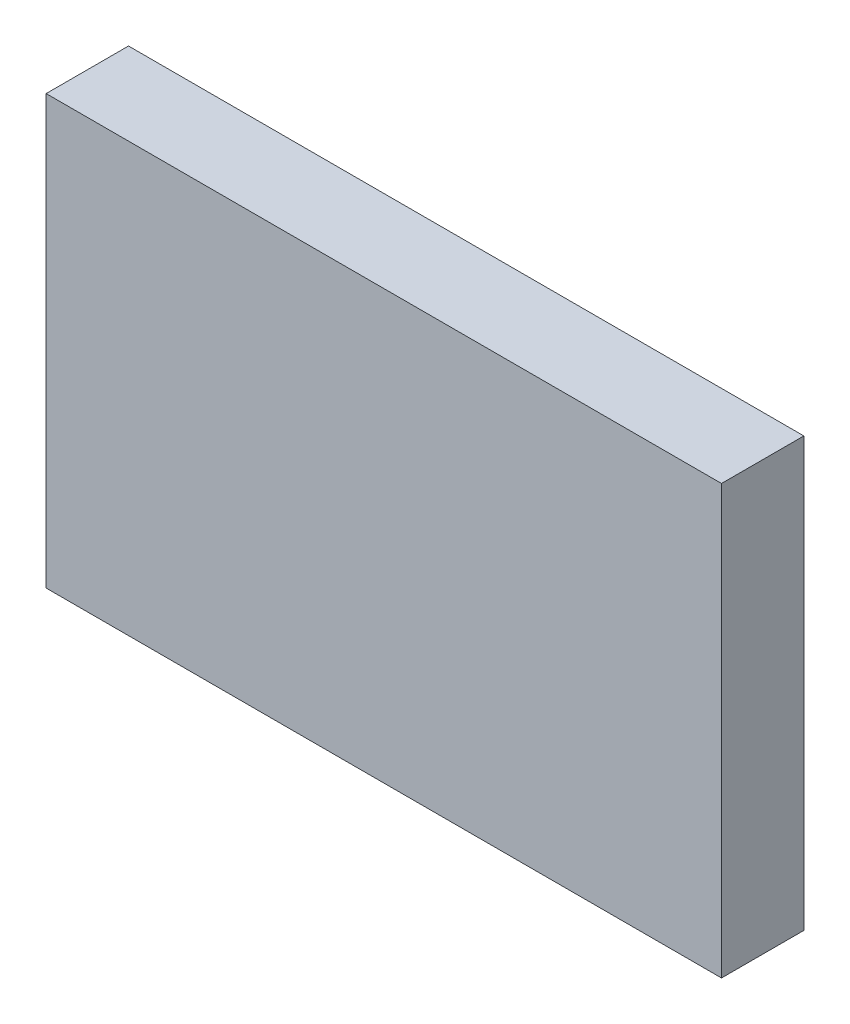
SolidWorks part; units mm, degrees
ref_plane "Front" through (0, 0, 0) normal (0, 0, 1) x (1, 0, 0)
ref_plane "Top" through (0, 0, 0) normal (0, 1, 0) x (1, 0, 0)
ref_plane "Right" through (0, 0, 0) normal (1, 0, 0) x (0, 0, -1)
sketch "Sketch1" plane through (0, 0, 0) normal (0, 0, 1) x (1, 0, 0)
  line L1 (-41, -26) -> (41, -26)
  line L2 (-41, -26) -> (-41, 26)
  line L3 (-41, 26) -> (41, 26)
  line L4 (41, -26) -> (41, 26)
  line L5 (-41, -26) -> (41, 26) construction
  line L6 (-41, 26) -> (41, -26) construction
  point P0 (0, 0)
  dimension "D1" = 82
  dimension "D2" = 52
extrude "Boss-Extrude1" add sketch "Sketch1" along normal blind 10
